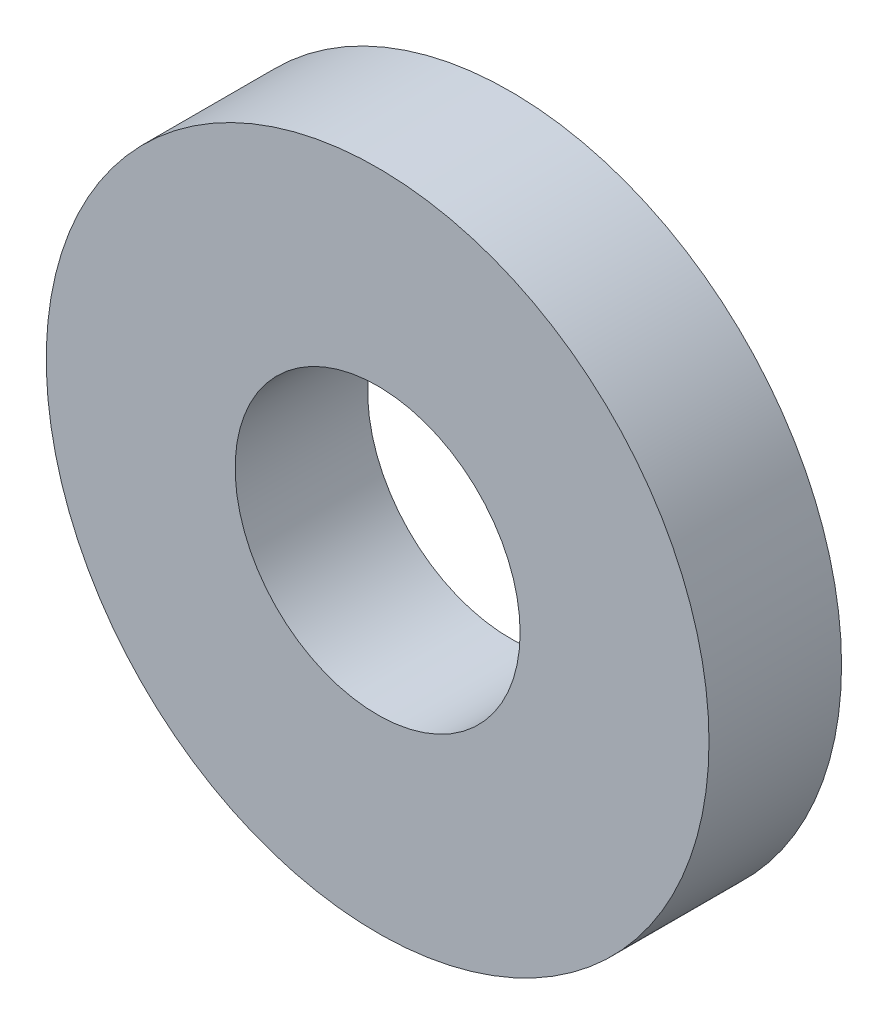
SolidWorks part; units mm, degrees
material "ABS"
ref_plane "前视基准面" through (0, 0, 0) normal (0, 0, 1) x (1, 0, 0)
ref_plane "上视基准面" through (0, 0, 0) normal (0, 1, 0) x (1, 0, 0)
ref_plane "右视基准面" through (0, 0, 0) normal (1, 0, 0) x (0, 0, -1)
sketch "草图1" plane through (0, 0, 0) normal (0, 0, 1) x (1, 0, 0)
  circle A0 centre (0, 0) radius 2.15
  circle A1 centre (0, 0) radius 5
  dimension "D1" = 4.3
  dimension "D2" = 10
extrude "凸台-拉伸1" add sketch "草图1" along normal blind 2
